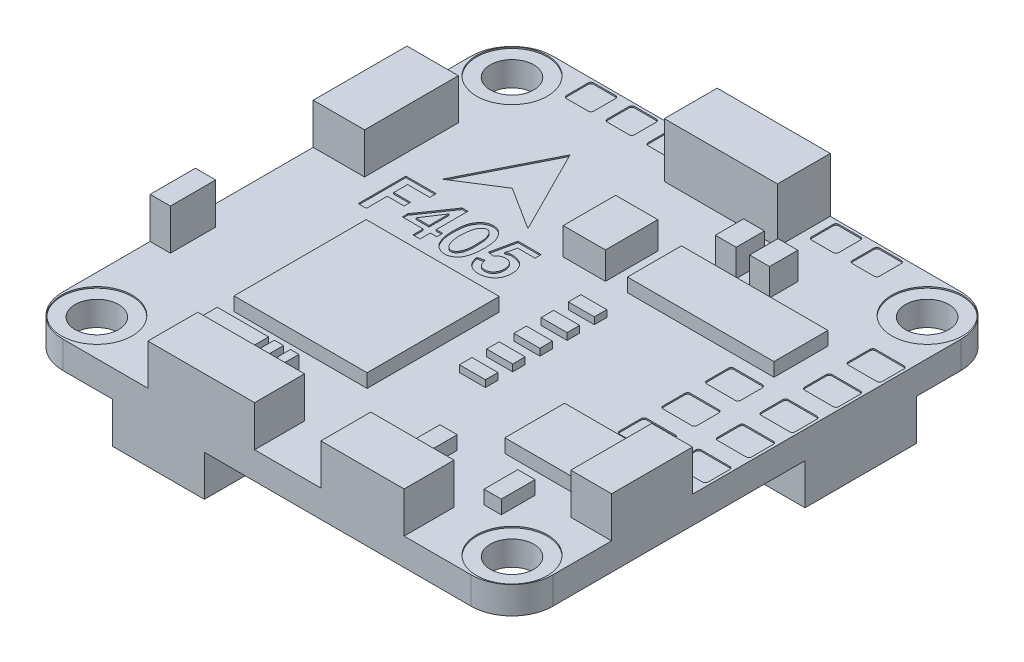
SolidWorks part; units mm, degrees
material "S-玻璃纤维"
ref_plane "前视基准面" through (0, 0, 0) normal (0, 0, 1) x (1, 0, 0)
ref_plane "上视基准面" through (0, 0, 0) normal (0, 1, 0) x (1, 0, 0)
ref_plane "右视基准面" through (0, 0, 0) normal (1, 0, 0) x (0, 0, -1)
sketch "草图1" plane through (0, 0, 0) normal (0, 1, 0) x (1, 0, 0)
  line L1 (18, -18) -> (-18, -18)
  line L2 (18, -18) -> (18, 18)
  line L3 (18, 18) -> (-18, 18)
  line L4 (-18, -18) -> (-18, 18)
  line L5 (18, -18) -> (-18, 18) construction
  line L6 (18, 18) -> (-18, -18) construction
  point P0 (0, 0)
  point P6 (0, 0)
  dimension "D1" = 36
  dimension "D2" = 36
extrude "凸台-拉伸1" add sketch "草图1" along normal blind 2
hole_wizard "M3 间隙孔1" positions "草图2" profile "草图3" hole size "M3" standard "GB" end condition through all
sketch "草图2" plane through (0, 2, 0) normal (0, 1, 0) x (1, 0, 0)
  point P0 (-15.25, 15.25)
  dimension "D1" = 15.25
  dimension "D2" = 15.25
sketch "草图3" plane through (-15.25, 2, -15.25) normal (1, 0, 0) x (0, 0, 1)
  line L0 (0, 0) -> (0, 2)
  line L1 (0, 2) -> (1.6, 2)
  line L2 (1.6, 2) -> (1.6, 0)
  line L5 (1.6, 0) -> (0, 0)
  line L11 (0, -6.35) -> (0, 107.95) construction
  dimension "通孔孔直径" = 3.2
  dimension "通孔孔深度" = 2
mirror "镜向1" about plane through (0, 0, 0) normal (0, 0, 1) of "M3 间隙孔1"
mirror "镜向2" about plane through (0, 0, 0) normal (1, 0, 0) of "镜向1", "M3 间隙孔1"
fillet "圆角1" radius 3 4 edges at (-18, 1, 18) (18, 1, 18) (18, 1, -18) (-18, 1, -18)
sketch "草图4" plane through (0, 2, 0) normal (0, 1, 0) x (1, 0, 0)
  circle A2 centre (-15.25, 15.25) radius 2.6
  circle A3 centre (-15.25, 15.25) radius 2.6
  circle A9 centre (15.25, 15.25) radius 2.6
  circle A10 centre (15.25, 15.25) radius 2.6
  circle A12 centre (-15.25, -15.25) radius 2.6
  circle A13 centre (-15.25, -15.25) radius 2.6
  circle A15 centre (15.25, -15.25) radius 2.6
  circle A16 centre (15.25, -15.25) radius 2.6
  dimension "D1" = 1
  dimension "D2" = 1
  dimension "D3" = 1
  dimension "D4" = 1
extrude "切除-拉伸1" cut sketch "草图4" against normal blind 0.1
sketch "草图5" plane through (0, 2, 0) normal (0, 1, 0) x (1, 0, 0)
  line L1 (-10.4576, -0.2555) -> (-0.6813, -0.2555)
  line L2 (-10.4576, -0.2555) -> (-10.4576, -9.9636)
  line L3 (-10.4576, -9.9636) -> (-0.6813, -9.9636)
  line L4 (-0.6813, -0.2555) -> (-0.6813, -9.9636)
  line L5 (2.7932, 9.6571) -> (13.5537, 9.6571)
  line L6 (2.7932, 9.6571) -> (2.7932, 5.6895)
  line L7 (2.7932, 5.6895) -> (13.5537, 5.6895)
  line L8 (13.5537, 9.6571) -> (13.5537, 5.6895)
  line L9 (8.5159, -4.6497) -> (13.5233, -4.6497)
  line L10 (8.5159, -4.6497) -> (8.5159, -9.0439)
  line L11 (8.5159, -9.0439) -> (13.5233, -9.0439)
  line L12 (13.5233, -4.6497) -> (13.5233, -9.0439)
  point P12 (14.0002, 4.4112)
  point P13 (2.7932, 4.9222)
  point P14 (13.5537, 5.6895)
extrude "凸台-拉伸2" add sketch "草图5" along normal blind 1
sketch "草图6" plane through (0, 2, 0) normal (0, 1, 0) x (1, 0, 0)
  line L0 (-15, -18) -> (15, -18) construction
  line L1 (-8.7487, -18) -> (-0.909, -18)
  line L2 (-8.7487, -18) -> (-8.7487, -14.3333)
  line L3 (-8.7487, -14.3333) -> (-0.909, -14.3333)
  line L4 (-0.909, -18) -> (-0.909, -14.3333)
  line L5 (18, -15) -> (18, 15) construction
  line L6 (3.957, -18) -> (10.0733, -18)
  line L7 (3.957, -18) -> (3.957, -14.3333)
  line L8 (3.957, -14.3333) -> (10.0733, -14.3333)
  line L9 (10.0733, -18) -> (10.0733, -14.3333)
  line L10 (18, -10.6838) -> (15, -10.6838)
  line L11 (18, -10.6838) -> (18, -4.7365)
  line L12 (18, -4.7365) -> (15, -4.7365)
  line L13 (15, -10.6838) -> (15, -4.7365)
  line L14 (-18, 15) -> (-18, -15) construction
  line L15 (-18, 10.2845) -> (-14.2268, 10.2845)
  line L16 (-18, 10.2845) -> (-18, 3.3932)
  line L17 (-18, 3.3932) -> (-14.2268, 3.3932)
  line L18 (-14.2268, 10.2845) -> (-14.2268, 3.3932)
  line L20 (-18, -5.2609) -> (-16.5105, -5.2609)
  line L21 (-18, -5.2609) -> (-18, -8.5863)
  line L22 (-18, -8.5863) -> (-16.5105, -8.5863)
  line L23 (-16.5105, -5.2609) -> (-16.5105, -8.5863)
extrude "凸台-拉伸3" add sketch "草图6" along normal blind 3
sketch "草图7" plane through (0, 2, 0) normal (0, 1, 0) x (1, 0, 0)
  line L0 (15, 18) -> (-15, 18) construction
  line L1 (-2.9295, 18) -> (5.3821, 18)
  line L2 (-2.9295, 18) -> (-2.9295, 14.1194)
  line L3 (-2.9295, 14.1194) -> (5.3821, 14.1194)
  line L4 (5.3821, 18) -> (5.3821, 14.1194)
extrude "凸台-拉伸4" add sketch "草图7" along normal blind 4
sketch "草图8" plane through (0, 0, 0) normal (0, -1, 0) x (1, 0, 0)
  line L0 (-18, -15) -> (-18, 15) construction
  line L1 (-18, 9.5208) -> (-2.2823, 9.5208)
  line L2 (-18, 9.5208) -> (-18, -4.9222)
  line L3 (-18, -4.9222) -> (-2.2823, -4.9222)
  line L4 (-2.2823, 9.5208) -> (-2.2823, -4.9222)
extrude "凸台-拉伸5" add sketch "草图8" along normal blind 2.5
sketch "草图9" plane through (0, 0, 0) normal (0, -1, 0) x (1, 0, 0)
  line L0 (-18, -15) -> (-18, -4.9222) construction
  line L1 (-13.6595, -12.0756) -> (-18, -12.0756)
  line L2 (-13.6595, -12.0756) -> (-13.6595, -6.2166)
  line L3 (-13.6595, -6.2166) -> (-18, -6.2166)
  line L4 (-18, -12.0756) -> (-18, -6.2166)
  line L5 (18, 15) -> (18, -15) construction
  line L6 (18, -11.7009) -> (14.1705, -11.7009)
  line L7 (18, -11.7009) -> (18, -3.5256)
  line L8 (18, -3.5256) -> (14.1705, -3.5256)
  line L9 (14.1705, -11.7009) -> (14.1705, -3.5256)
  line L10 (-15, 18) -> (15, 18) construction
  line L11 (-4.5986, 18) -> (-11.3432, 18)
  line L12 (-4.5986, 18) -> (-4.5986, 14.6985)
  line L13 (-4.5986, 14.6985) -> (-11.3432, 14.6985)
  line L14 (-11.3432, 18) -> (-11.3432, 14.6985)
extrude "凸台-拉伸6" add sketch "草图9" along normal blind 3
sketch "草图10" plane through (0, 0, 0) normal (0, -1, 0) x (1, 0, 0)
  line L0 (15, -18) -> (-15, -18) construction
  line L1 (-3.0317, -18) -> (5.0755, -18)
  line L2 (-3.0317, -18) -> (-3.0317, -13.4381)
  line L3 (-3.0317, -13.4381) -> (5.0755, -13.4381)
  line L4 (5.0755, -18) -> (5.0755, -13.4381)
extrude "凸台-拉伸7" add sketch "草图10" along normal blind 4
sketch "草图11" plane through (0, 0, 0) normal (0, -1, 0) x (1, 0, 0)
  circle A2 centre (-15.25, 15.25) radius 2.6
  circle A3 centre (-15.25, 15.25) radius 2.6
  circle A5 centre (15.25, 15.25) radius 2.6
  circle A6 centre (15.25, 15.25) radius 2.6
  circle A8 centre (-15.25, -15.25) radius 2.6
  circle A9 centre (-15.25, -15.25) radius 2.6
  circle A11 centre (15.25, -15.25) radius 2.6
  circle A12 centre (15.25, -15.25) radius 2.6
  dimension "D1" = 1
  dimension "D2" = 1
  dimension "D3" = 1
  dimension "D4" = 1
extrude "切除-拉伸2" cut sketch "草图11" against normal blind 0.1
sketch "草图12" plane through (0, 2, 0) normal (0, 1, 0) x (1, 0, 0)
  line L1 (-1.8394, 9.4527) -> (1.2604, 9.4527)
  line L2 (-1.8394, 9.4527) -> (-1.8394, 5.6035)
  line L3 (-1.8394, 5.6035) -> (1.2604, 5.6035)
  line L4 (1.2604, 9.4527) -> (1.2604, 5.6035)
  line L5 (4.3602, 12.6547) -> (5.893, 12.6547)
  line L6 (4.3602, 12.6547) -> (4.3602, 10.5768)
  line L7 (4.3602, 10.5768) -> (5.893, 10.5768)
  line L8 (5.893, 12.6547) -> (5.893, 10.5768)
  line L9 (6.8809, 12.6547) -> (8.3456, 12.6547)
  line L10 (6.8809, 12.6547) -> (6.8809, 10.5768)
  line L11 (6.8809, 10.5768) -> (8.3456, 10.5768)
  line L12 (8.3456, 12.6547) -> (8.3456, 10.5768)
extrude "凸台-拉伸8" add sketch "草图12" along normal blind 2
sketch "草图13" plane through (0, 2, 0) normal (0, 1, 0) x (1, 0, 0)
  line L1 (5.3046, -10.5967) -> (6.5718, -10.5967)
  line L2 (5.3046, -10.5967) -> (5.3046, -13.0747)
  line L3 (5.3046, -13.0747) -> (6.5718, -13.0747)
  line L4 (6.5718, -10.5967) -> (6.5718, -13.0747)
  line L5 (11.0211, -10.5967) -> (12.2883, -10.5967)
  line L6 (11.0211, -10.5967) -> (11.0211, -13.0747)
  line L7 (11.0211, -13.0747) -> (12.2883, -13.0747)
  line L8 (12.2883, -10.5967) -> (12.2883, -13.0747)
  line L9 (-10.3522, -11.3007) -> (-6.5788, -11.3007)
  line L10 (-10.3522, -11.3007) -> (-10.3522, -12.596)
  line L11 (-10.3522, -12.596) -> (-6.5788, -12.596)
  line L12 (-6.5788, -11.3007) -> (-6.5788, -12.596)
  line L13 (-6.1564, -11.3007) -> (-5.4805, -11.3007)
  line L14 (-6.1564, -11.3007) -> (-6.1564, -12.596)
  line L15 (-6.1564, -12.596) -> (-5.4805, -12.596)
  line L16 (-5.4805, -11.3007) -> (-5.4805, -12.596)
  line L17 (-4.9737, -11.3007) -> (-4.3542, -11.3007)
  line L18 (-4.9737, -11.3007) -> (-4.9737, -12.596)
  line L19 (-4.9737, -12.596) -> (-4.3542, -12.596)
  line L20 (-4.3542, -11.3007) -> (-4.3542, -12.596)
extrude "凸台-拉伸9" add sketch "草图13" along normal blind 1
sketch "草图14" plane through (0, 2, 0) normal (0, 1, 0) x (1, 0, 0)
  line L1 (-11.8, 15.8) -> (-10.2, 15.8)
  line L2 (-12, 16) -> (-12, 17.6)
  line L3 (-11.8, 17.8) -> (-10.2, 17.8)
  line L4 (-10, 16) -> (-10, 17.6)
  line L5 (-12, 15.8) -> (-10, 17.8) construction
  line L6 (-12, 17.8) -> (-10, 15.8) construction
  line L7 (-2.9295, 18) -> (-15, 18) construction
  line L8 (-18, 15) -> (-18, 10.2845) construction
  line L9 (-8.8, 15.8) -> (-7.2, 15.8)
  line L10 (-9, 16) -> (-9, 17.6)
  line L11 (-8.8, 17.8) -> (-7.2, 17.8)
  line L12 (-7, 16) -> (-7, 17.6)
  line L13 (-9, 15.8) -> (-7, 17.8) construction
  line L14 (-9, 17.8) -> (-7, 15.8) construction
  line L15 (-5.8, 15.8) -> (-4.2, 15.8)
  line L16 (-6, 16) -> (-6, 17.6)
  line L17 (-5.8, 17.8) -> (-4.2, 17.8)
  line L18 (-4, 16) -> (-4, 17.6)
  line L19 (-6, 15.8) -> (-4, 17.8) construction
  line L20 (-6, 17.8) -> (-4, 15.8) construction
  line L21 (-2.8, 15.8) -> (-1.2, 15.8) [skipped]
  line L22 (-3, 16) -> (-3, 17.6) [skipped]
  line L23 (-2.8, 17.8) -> (-1.2, 17.8) [skipped]
  line L24 (-1, 16) -> (-1, 17.6) [skipped]
  line L25 (-3, 15.8) -> (-1, 17.8) construction
  line L26 (-3, 17.8) -> (-1, 15.8) construction
  line L27 (0.2, 15.8) -> (1.8, 15.8) [skipped]
  line L28 (0, 16) -> (0, 17.6) [skipped]
  line L29 (0.2, 17.8) -> (1.8, 17.8) [skipped]
  line L30 (2, 16) -> (2, 17.6) [skipped]
  line L31 (0, 15.8) -> (2, 17.8) construction
  line L32 (0, 17.8) -> (2, 15.8) construction
  line L33 (3.2, 15.8) -> (4.8, 15.8) [skipped]
  line L34 (3, 16) -> (3, 17.6) [skipped]
  line L35 (3.2, 17.8) -> (4.8, 17.8) [skipped]
  line L36 (5, 16) -> (5, 17.6) [skipped]
  line L37 (3, 15.8) -> (5, 17.8) construction
  line L38 (3, 17.8) -> (5, 15.8) construction
  line L39 (6.2, 15.8) -> (7.8, 15.8)
  line L40 (6, 16) -> (6, 17.6)
  line L41 (6.2, 17.8) -> (7.8, 17.8)
  line L42 (8, 16) -> (8, 17.6)
  line L43 (6, 15.8) -> (8, 17.8) construction
  line L44 (6, 17.8) -> (8, 15.8) construction
  line L45 (9.2, 15.8) -> (10.8, 15.8)
  line L46 (9, 16) -> (9, 17.6)
  line L47 (9.2, 17.8) -> (10.8, 17.8)
  line L48 (11, 16) -> (11, 17.6)
  line L49 (9, 15.8) -> (11, 17.8) construction
  line L50 (9, 17.8) -> (11, 15.8) construction
  arc A0 (-12, 17.6) -> (-11.8, 17.8) centre (-11.8, 17.6) cw
  arc A1 (-11.8, 15.8) -> (-12, 16) centre (-11.8, 16) cw
  arc A2 (-10.2, 15.8) -> (-10, 16) centre (-10.2, 16) ccw
  arc A3 (-10.2, 17.8) -> (-10, 17.6) centre (-10.2, 17.6) cw
  arc A4 (-9, 17.6) -> (-8.8, 17.8) centre (-8.8, 17.6) cw
  arc A5 (-8.8, 15.8) -> (-9, 16) centre (-8.8, 16) cw
  arc A6 (-7.2, 15.8) -> (-7, 16) centre (-7.2, 16) ccw
  arc A7 (-7.2, 17.8) -> (-7, 17.6) centre (-7.2, 17.6) cw
  arc A8 (-6, 17.6) -> (-5.8, 17.8) centre (-5.8, 17.6) cw
  arc A9 (-5.8, 15.8) -> (-6, 16) centre (-5.8, 16) cw
  arc A10 (-4.2, 15.8) -> (-4, 16) centre (-4.2, 16) ccw
  arc A11 (-4.2, 17.8) -> (-4, 17.6) centre (-4.2, 17.6) cw
  arc A12 (-3, 17.6) -> (-2.8, 17.8) centre (-2.8, 17.6) cw [skipped]
  arc A13 (-2.8, 15.8) -> (-3, 16) centre (-2.8, 16) cw [skipped]
  arc A14 (-1.2, 15.8) -> (-1, 16) centre (-1.2, 16) ccw [skipped]
  arc A15 (-1.2, 17.8) -> (-1, 17.6) centre (-1.2, 17.6) cw [skipped]
  arc A16 (0, 17.6) -> (0.2, 17.8) centre (0.2, 17.6) cw [skipped]
  arc A17 (0.2, 15.8) -> (0, 16) centre (0.2, 16) cw [skipped]
  arc A18 (1.8, 15.8) -> (2, 16) centre (1.8, 16) ccw [skipped]
  arc A19 (1.8, 17.8) -> (2, 17.6) centre (1.8, 17.6) cw [skipped]
  arc A20 (3, 17.6) -> (3.2, 17.8) centre (3.2, 17.6) cw [skipped]
  arc A21 (3.2, 15.8) -> (3, 16) centre (3.2, 16) cw [skipped]
  arc A22 (4.8, 15.8) -> (5, 16) centre (4.8, 16) ccw [skipped]
  arc A23 (4.8, 17.8) -> (5, 17.6) centre (4.8, 17.6) cw [skipped]
  arc A24 (6, 17.6) -> (6.2, 17.8) centre (6.2, 17.6) cw
  arc A25 (6.2, 15.8) -> (6, 16) centre (6.2, 16) cw
  arc A26 (7.8, 15.8) -> (8, 16) centre (7.8, 16) ccw
  arc A27 (7.8, 17.8) -> (8, 17.6) centre (7.8, 17.6) cw
  arc A28 (9, 17.6) -> (9.2, 17.8) centre (9.2, 17.6) cw
  arc A29 (9.2, 15.8) -> (9, 16) centre (9.2, 16) cw
  arc A30 (10.8, 15.8) -> (11, 16) centre (10.8, 16) ccw
  arc A31 (10.8, 17.8) -> (11, 17.6) centre (10.8, 17.6) cw
  point P0 (-11, 16.8)
  point P6 (-8, 16.8)
  point P40 (-5, 16.8)
  point P57 (-2, 16.8)
  point P74 (1, 16.8)
  point P91 (4, 16.8)
  point P108 (7, 16.8)
  point P125 (10, 16.8)
  dimension "D5" = 0.2
  dimension "D1" = 2
  dimension "D2" = 2
  dimension "D3" = 0.2
  dimension "D4" = 6
  dimension "D6" = 8
extrude "切除-拉伸3" cut sketch "草图14" against normal blind 0.1
sketch "草图15" plane through (0, 2, 0) normal (0, 1, 0) x (1, 0, 0)
  line L0 (18, -4.7365) -> (18, 15) construction
  line L1 (15.5, 11.2) -> (17.6, 11.2)
  line L2 (15.3, 11) -> (15.3, 9.4)
  line L3 (15.5, 9.2) -> (17.6, 9.2)
  line L4 (17.8, 11) -> (17.8, 9.4)
  line L5 (15.3, 11.2) -> (17.8, 9.2) construction
  line L6 (15.3, 9.2) -> (17.8, 11.2) construction
  line L7 (15, 18) -> (5.3821, 18) construction
  line L8 (11.5, 11.2) -> (13.6, 11.2) [skipped]
  line L9 (11.3, 11) -> (11.3, 9.4) [skipped]
  line L10 (11.5, 9.2) -> (13.6, 9.2) [skipped]
  line L11 (13.8, 11) -> (13.8, 9.4) [skipped]
  line L12 (11.3, 11.2) -> (13.8, 9.2) construction
  line L13 (11.3, 9.2) -> (13.8, 11.2) construction
  line L14 (11.5, 8) -> (13.6, 8) [skipped]
  line L15 (11.3, 7.8) -> (11.3, 6.2) [skipped]
  line L16 (11.5, 6) -> (13.6, 6) [skipped]
  line L17 (13.8, 7.8) -> (13.8, 6.2) [skipped]
  line L18 (11.3, 8) -> (13.8, 6) construction
  line L19 (11.3, 6) -> (13.8, 8) construction
  line L20 (11.5, 4.8) -> (13.6, 4.8)
  line L21 (11.3, 4.6) -> (11.3, 3)
  line L22 (11.5, 2.8) -> (13.6, 2.8)
  line L23 (13.8, 4.6) -> (13.8, 3)
  line L24 (11.3, 4.8) -> (13.8, 2.8) construction
  line L25 (11.3, 2.8) -> (13.8, 4.8) construction
  line L26 (11.5, 1.6) -> (13.6, 1.6)
  line L27 (11.3, 1.4) -> (11.3, -0.2)
  line L28 (11.5, -0.4) -> (13.6, -0.4)
  line L29 (13.8, 1.4) -> (13.8, -0.2)
  line L30 (11.3, 1.6) -> (13.8, -0.4) construction
  line L31 (11.3, -0.4) -> (13.8, 1.6) construction
  line L32 (11.5, -1.6) -> (13.6, -1.6)
  line L33 (11.3, -1.8) -> (11.3, -3.4)
  line L34 (11.5, -3.6) -> (13.6, -3.6)
  line L35 (13.8, -1.8) -> (13.8, -3.4)
  line L36 (11.3, -1.6) -> (13.8, -3.6) construction
  line L37 (11.3, -3.6) -> (13.8, -1.6) construction
  line L38 (15.5, 8) -> (17.6, 8)
  line L39 (15.3, 7.8) -> (15.3, 6.2)
  line L40 (15.5, 6) -> (17.6, 6)
  line L41 (17.8, 7.8) -> (17.8, 6.2)
  line L42 (15.3, 8) -> (17.8, 6) construction
  line L43 (15.3, 6) -> (17.8, 8) construction
  line L44 (15.5, 4.8) -> (17.6, 4.8)
  line L45 (15.3, 4.6) -> (15.3, 3)
  line L46 (15.5, 2.8) -> (17.6, 2.8)
  line L47 (17.8, 4.6) -> (17.8, 3)
  line L48 (15.3, 4.8) -> (17.8, 2.8) construction
  line L49 (15.3, 2.8) -> (17.8, 4.8) construction
  line L50 (15.5, 1.6) -> (17.6, 1.6)
  line L51 (15.3, 1.4) -> (15.3, -0.2)
  line L52 (15.5, -0.4) -> (17.6, -0.4)
  line L53 (17.8, 1.4) -> (17.8, -0.2)
  line L54 (15.3, 1.6) -> (17.8, -0.4) construction
  line L55 (15.3, -0.4) -> (17.8, 1.6) construction
  line L56 (15.5, -1.6) -> (17.6, -1.6)
  line L57 (15.3, -1.8) -> (15.3, -3.4)
  line L58 (15.5, -3.6) -> (17.6, -3.6)
  line L59 (17.8, -1.8) -> (17.8, -3.4)
  line L60 (15.3, -1.6) -> (17.8, -3.6) construction
  line L61 (15.3, -3.6) -> (17.8, -1.6) construction
  arc A0 (15.3, 9.4) -> (15.5, 9.2) centre (15.5, 9.4) ccw
  arc A1 (17.6, 9.2) -> (17.8, 9.4) centre (17.6, 9.4) ccw
  arc A2 (17.6, 11.2) -> (17.8, 11) centre (17.6, 11) cw
  arc A3 (15.5, 11.2) -> (15.3, 11) centre (15.5, 11) ccw
  arc A4 (11.3, 9.4) -> (11.5, 9.2) centre (11.5, 9.4) ccw [skipped]
  arc A5 (13.6, 9.2) -> (13.8, 9.4) centre (13.6, 9.4) ccw [skipped]
  arc A6 (13.6, 11.2) -> (13.8, 11) centre (13.6, 11) cw [skipped]
  arc A7 (11.5, 11.2) -> (11.3, 11) centre (11.5, 11) ccw [skipped]
  arc A8 (11.3, 6.2) -> (11.5, 6) centre (11.5, 6.2) ccw [skipped]
  arc A9 (13.6, 6) -> (13.8, 6.2) centre (13.6, 6.2) ccw [skipped]
  arc A10 (13.6, 8) -> (13.8, 7.8) centre (13.6, 7.8) cw [skipped]
  arc A11 (11.5, 8) -> (11.3, 7.8) centre (11.5, 7.8) ccw [skipped]
  arc A12 (11.3, 3) -> (11.5, 2.8) centre (11.5, 3) ccw
  arc A13 (13.6, 2.8) -> (13.8, 3) centre (13.6, 3) ccw
  arc A14 (13.6, 4.8) -> (13.8, 4.6) centre (13.6, 4.6) cw
  arc A15 (11.5, 4.8) -> (11.3, 4.6) centre (11.5, 4.6) ccw
  arc A16 (11.3, -0.2) -> (11.5, -0.4) centre (11.5, -0.2) ccw
  arc A17 (13.6, -0.4) -> (13.8, -0.2) centre (13.6, -0.2) ccw
  arc A18 (13.6, 1.6) -> (13.8, 1.4) centre (13.6, 1.4) cw
  arc A19 (11.5, 1.6) -> (11.3, 1.4) centre (11.5, 1.4) ccw
  arc A20 (11.3, -3.4) -> (11.5, -3.6) centre (11.5, -3.4) ccw
  arc A21 (13.6, -3.6) -> (13.8, -3.4) centre (13.6, -3.4) ccw
  arc A22 (13.6, -1.6) -> (13.8, -1.8) centre (13.6, -1.8) cw
  arc A23 (11.5, -1.6) -> (11.3, -1.8) centre (11.5, -1.8) ccw
  arc A24 (15.3, 6.2) -> (15.5, 6) centre (15.5, 6.2) ccw
  arc A25 (17.6, 6) -> (17.8, 6.2) centre (17.6, 6.2) ccw
  arc A26 (17.6, 8) -> (17.8, 7.8) centre (17.6, 7.8) cw
  arc A27 (15.5, 8) -> (15.3, 7.8) centre (15.5, 7.8) ccw
  arc A28 (15.3, 3) -> (15.5, 2.8) centre (15.5, 3) ccw
  arc A29 (17.6, 2.8) -> (17.8, 3) centre (17.6, 3) ccw
  arc A30 (17.6, 4.8) -> (17.8, 4.6) centre (17.6, 4.6) cw
  arc A31 (15.5, 4.8) -> (15.3, 4.6) centre (15.5, 4.6) ccw
  arc A32 (15.3, -0.2) -> (15.5, -0.4) centre (15.5, -0.2) ccw
  arc A33 (17.6, -0.4) -> (17.8, -0.2) centre (17.6, -0.2) ccw
  arc A34 (17.6, 1.6) -> (17.8, 1.4) centre (17.6, 1.4) cw
  arc A35 (15.5, 1.6) -> (15.3, 1.4) centre (15.5, 1.4) ccw
  arc A36 (15.3, -3.4) -> (15.5, -3.6) centre (15.5, -3.4) ccw
  arc A37 (17.6, -3.6) -> (17.8, -3.4) centre (17.6, -3.4) ccw
  arc A38 (17.6, -1.6) -> (17.8, -1.8) centre (17.6, -1.8) cw
  arc A39 (15.5, -1.6) -> (15.3, -1.8) centre (15.5, -1.8) ccw
  point P0 (16.55, 10.2)
  point P24 (12.55, 10.2)
  point P41 (12.55, 7)
  point P58 (12.55, 3.8)
  point P75 (12.55, 0.6)
  point P92 (12.55, -2.6)
  point P109 (16.55, 7)
  point P126 (16.55, 3.8)
  point P143 (16.55, 0.6)
  point P160 (16.55, -2.6)
  dimension "D5" = 0.2
  dimension "D1" = 2
  dimension "D2" = 2.5
  dimension "D3" = 0.2
  dimension "D4" = 6.8
  dimension "D6" = 2
  dimension "D7" = 5
extrude "切除-拉伸4" cut sketch "草图15" against normal blind 0.1
sketch "草图16" plane through (0, 2, 0) normal (0, 1, 0) x (1, 0, 0)
  line L0 (-8.0873, 8.104) -> (-8.0873, 12.3509) construction
  line L1 (-8.0873, 12.3509) -> (-11.233, 6.11)
  line L2 (-11.233, 6.11) -> (-8.0873, 8.104)
  line L3 (-4.9417, 6.11) -> (-8.0873, 8.104)
  line L4 (-8.0873, 12.3509) -> (-4.9417, 6.11)
  line L5 (-13.0073, 1.3691) -> (1.5918, 1.3691) construction
  text T0 "F405" font "黑体" height 3.5
  point P6 (1.2547, 1.4068)
  point P8 (-13.1315, 1.2604)
  point P9 (1.5918, 1.307)
  point P10 (-13.0073, 1.3691)
extrude "切除-拉伸5" cut sketch "草图16" against normal blind 0.1
sketch "草图17" plane through (0, 2, 0) normal (0, 1, 0) x (1, 0, 0)
  line L0 (1.7032, 1.3553) -> (3.6108, 1.3553)
  line L1 (1.7032, 3.3553) -> (3.6108, 3.3553)
  line L2 (1.7032, 3.3553) -> (1.7032, 2.4356)
  line L3 (1.7032, 2.4356) -> (3.6108, 2.4356)
  line L4 (3.6108, 3.3553) -> (3.6108, 2.4356)
  line L5 (1.7032, 1.3553) -> (1.7032, 0.4356)
  line L6 (1.7032, 0.4356) -> (3.6108, 0.4356)
  line L7 (3.6108, 1.3553) -> (3.6108, 0.4356)
  line L8 (1.7032, -0.6447) -> (3.6108, -0.6447)
  line L9 (1.7032, -0.6447) -> (1.7032, -1.5644)
  line L10 (1.7032, -1.5644) -> (3.6108, -1.5644)
  line L11 (3.6108, -0.6447) -> (3.6108, -1.5644)
  line L12 (1.7032, -2.6447) -> (3.6108, -2.6447)
  line L13 (1.7032, -2.6447) -> (1.7032, -3.5644)
  line L14 (1.7032, -3.5644) -> (3.6108, -3.5644)
  line L15 (3.6108, -2.6447) -> (3.6108, -3.5644)
  line L16 (1.7032, -4.6447) -> (3.6108, -4.6447)
  line L17 (1.7032, -4.6447) -> (1.7032, -5.5644)
  line L18 (1.7032, -5.5644) -> (3.6108, -5.5644)
  line L19 (3.6108, -4.6447) -> (3.6108, -5.5644)
  dimension "D1" = 5
extrude "凸台-拉伸10" add sketch "草图17" along normal blind 0.5
